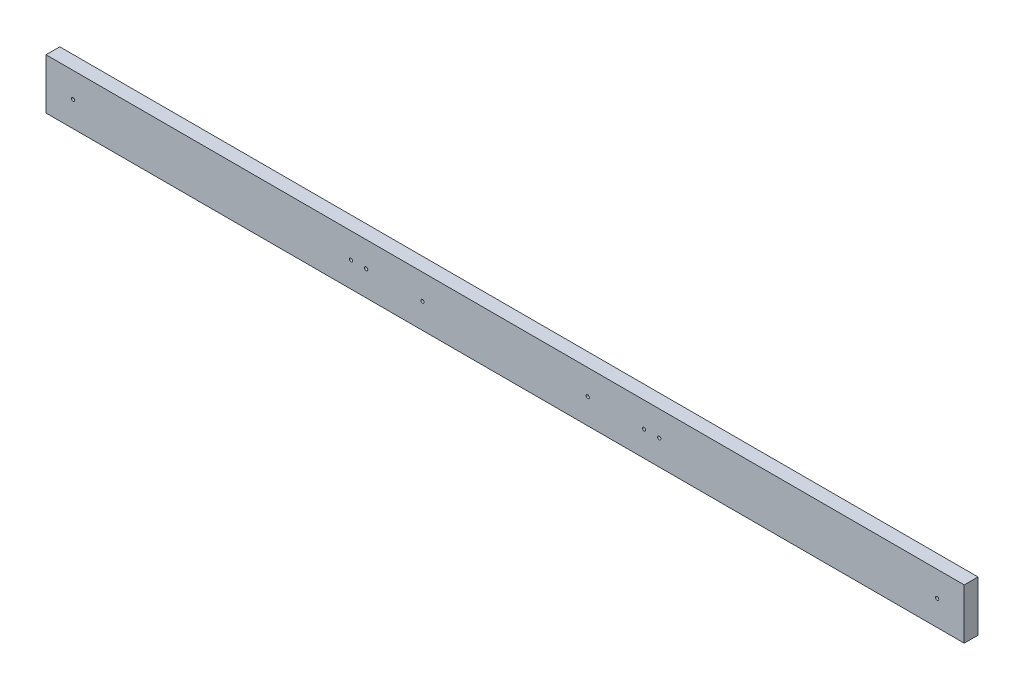
SolidWorks part; units mm, degrees
ref_plane "Front Plane" through (0, 0, 0) normal (0, 0, 1) x (1, 0, 0)
ref_plane "Top Plane" through (0, 0, 0) normal (0, 1, 0) x (1, 0, 0)
ref_plane "Right Plane" through (0, 0, 0) normal (1, 0, 0) x (0, 0, -1)
sketch "Sketch1" plane through (0, 0, 0) normal (0, 0, 1) x (1, 0, 0)
  line L1 (0, 0) -> (2540, 0)
  line L2 (0, 0) -> (0, -139.7)
  line L3 (0, -139.7) -> (2540, -139.7)
  line L4 (2540, 0) -> (2540, -139.7)
  dimension "D1" = 2540
  dimension "D2" = 139.7
extrude "Boss-Extrude1" add sketch "Sketch1" along normal blind 38.1
sketch "Sketch2" plane through (0, 0, 38.1) normal (0, 0, 1) x (1, 0, 0)
  line L0 (24.0114, -67.4433) -> (24.0114, -72.4471)
  line L1 (2540, 0) -> (0, 0) construction
  line L2 (15.0114, -67.3481) -> (15.0114, -72.3519)
  line L3 (0, 0) -> (0, -139.7) construction
  arc A0 (24.0114, -67.4433) -> (15.0114, -67.3481) centre (19.5109, -67.4433) ccw
  arc A1 (24.0114, -72.4471) -> (15.0114, -72.3519) centre (19.5109, -72.4471) cw
  point P8 (15.0114, -69.85)
  dimension "D3" = 4.5005
  dimension "D5" = 4.5005
  dimension "D1" = 5.0038
  dimension "D2" = 9
  dimension "D4" = 15.0114
  dimension "D6" = 69.85
sketch "Sketch4" plane through (0, 0, 38.1) normal (0, 0, 1) x (1, 0, 0)
  line L0 (0, -69.85) -> (2540, -69.85)
  line L1 (0, 0) -> (0, -139.7) construction
  line L2 (2540, -139.7) -> (2540, 0) construction
  line L3 (1270, -139.7) -> (1270, 0)
  line L4 (2540, 0) -> (0, 0) construction
  line L5 (0, -139.7) -> (2540, -139.7) construction
  point P10 (1211.58, 0)
  point P13 (1211.58, -139.7)
sketch "Sketch5" plane through (0, 0, 38.1) normal (0, 0, 1) x (1, 0, 0)
  line L0 (0, -69.85) -> (2540, -69.85) construction
  line L1 (1654.3604, -69.85) -> (885.6396, -69.85) construction
  line L3 (1270, -139.7) -> (1270, 0) construction
  line L4 (1041.4, -69.85) -> (1498.6, -69.85) construction
  circle A0 centre (1654.3604, -69.85) radius 4.4996
  circle A1 centre (885.6396, -69.85) radius 4.4996
  circle A2 centre (1041.4, -69.85) radius 4.4996
  circle A3 centre (1498.6, -69.85) radius 4.4996
  point P8 (1270, -69.85)
  point P13 (1044.6855, -69.85)
  point P16 (1270, -69.85)
  dimension "D2" = 8.9992
  dimension "D3" = 8.9992
  dimension "D5" = 8.9992
  dimension "D6" = 8.9992
  dimension "D1" = 768.7208
  dimension "D4" = 457.2
extrude "hinge and middle panel bolt thru holes" cut sketch "Sketch5" against normal through all
sketch "Sketch6" plane through (0, 0, 38.1) normal (0, 0, 1) x (1, 0, 0)
  point P0 (885.6396, -69.85)
  point P1 (1041.4, -69.85)
  point P3 (1654.3604, -69.85)
sketch "Sketch7" plane through (0, 0, 38.1) normal (0, 0, 1) x (1, 0, 0)
  line L0 (0, -69.85) -> (2540, -69.85) construction
  line L1 (0, 0) -> (2540, 0) construction
  line L2 (1270, 0) -> (1270, -139.7) construction
  circle A0 centre (1696.3604, -69.85) radius 4.4996
  circle A1 centre (2465.0812, -69.85) radius 4.4996
  circle A2 centre (74.9188, -69.85) radius 4.4996
  circle A3 centre (843.6396, -69.85) radius 4.4996
  point P12 (2465.0812, -69.85)
  point P13 (1696.3604, -69.85)
  dimension "D2" = 8.9992
  dimension "D3" = 8.9992
  dimension "D1" = 768.7208
  dimension "D4" = 42
extrude "Cut-Extrude2" cut sketch "Sketch7" against normal through all
sketch "Sketch8" plane through (0, 0, 38.1) normal (0, 0, 1) x (1, 0, 0)
  point P0 (843.6396, -69.85)
  point P1 (74.9188, -69.85)
  point P3 (2465.0812, -69.85)
  point P5 (1696.3604, -69.85)
